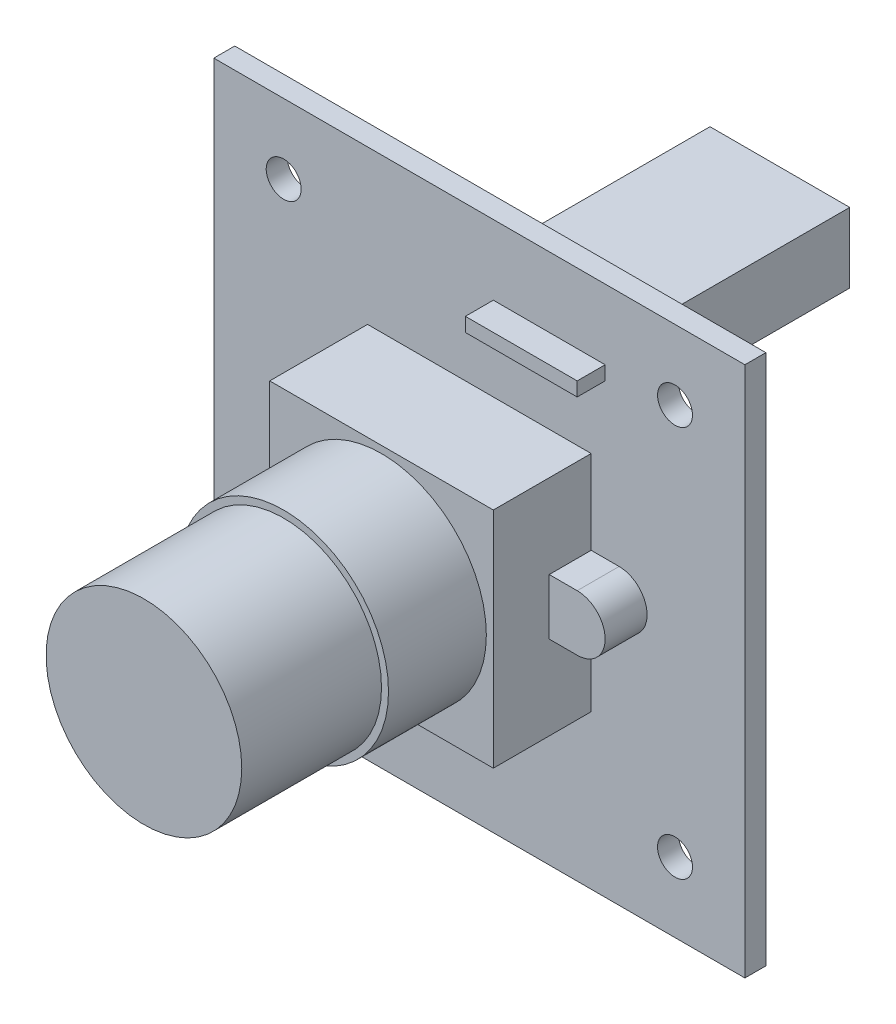
SolidWorks part; units mm, degrees
ref_plane "前视" through (0, 0, 0) normal (0, 0, 1) x (1, 0, 0)
ref_plane "上视" through (0, 0, 0) normal (0, 1, 0) x (1, 0, 0)
ref_plane "右视" through (0, 0, 0) normal (1, 0, 0) x (0, 0, -1)
sketch "草图1" plane through (0, 0, 0) normal (0, 0, 1) x (1, 0, 0)
  line L1 (-19, -19) -> (19, -19)
  line L2 (-19, -19) -> (-19, 19)
  line L3 (-19, 19) -> (19, 19)
  line L4 (19, -19) -> (19, 19)
  line L5 (-19, -19) -> (19, 19) construction
  line L6 (-19, 19) -> (19, -19) construction
  line L7 (-14, -14) -> (14, -14) construction
  line L8 (-14, -14) -> (-14, 14) construction
  line L9 (-14, 14) -> (14, 14) construction
  line L10 (14, -14) -> (14, 14) construction
  line L11 (-14, -14) -> (14, 14) construction
  line L12 (-14, 14) -> (14, -14) construction
  circle A0 centre (-14, 14) radius 1.25
  circle A1 centre (14, 14) radius 1.25
  circle A2 centre (14, -14) radius 1.25
  circle A3 centre (-14, -14) radius 1.25
  point P0 (0, 0)
  point P6 (0, 0)
  dimension "D3" = 2.5
  dimension "D1" = 38
  dimension "D2" = 38
  dimension "D4" = 28
extrude "凸台-拉伸1" add sketch "草图1" along normal blind 1.5
sketch "草图2" plane through (0, 0, 1.5) normal (0, 0, 1) x (1, 0, 0)
  line L1 (8, -8) -> (-8, -8)
  line L2 (8, -8) -> (8, 8)
  line L3 (8, 8) -> (-8, 8)
  line L4 (-8, -8) -> (-8, 8)
  line L5 (8, -8) -> (-8, 8) construction
  line L6 (8, 8) -> (-8, -8) construction
  point P0 (0, 0)
  dimension "D1" = 16
  dimension "D2" = 16
extrude "凸台-拉伸2" add sketch "草图2" along normal blind 7
sketch "草图3" plane through (0, 0, 8.5) normal (0, 0, 1) x (1, 0, 0)
  circle A0 centre (0, 0) radius 7.5
  dimension "D1" = 15
extrude "凸台-拉伸3" add sketch "草图3" along normal blind 7
sketch "草图5" plane through (0, 0, 1.5) normal (0, 0, 1) x (1, 0, 0)
  line L0 (10, 0) -> (-10, 0) construction
  line L1 (10, -2) -> (-10, -2)
  line L2 (10, 2) -> (-10, 2)
  arc A0 (10, -2) -> (10, 2) centre (10, 0) ccw
  arc A1 (-10, 2) -> (-10, -2) centre (-10, 0) ccw
  point P2 (0, 0)
  dimension "D1" = 20
  dimension "D2" = 4
extrude "凸台-拉伸4" add sketch "草图5" along normal blind 3
sketch "草图6" plane through (0, 0, 0) normal (0, 0, -1) x (-1, 0, 0)
  line L1 (-10, 11) -> (0, 11)
  line L2 (-10, 11) -> (-10, 16)
  line L3 (-10, 16) -> (0, 16)
  line L4 (0, 11) -> (0, 16)
  line L5 (-19, 19) -> (19, 19) construction
  line L6 (-19, -19) -> (-19, 19) construction
  dimension "D1" = 9
  dimension "D2" = 3
  dimension "D3" = 10
  dimension "D4" = 5
extrude "凸台-拉伸5" add sketch "草图6" along normal blind 15
sketch "草图7" plane through (0, 0, 15.5) normal (0, 0, 1) x (1, 0, 0)
  circle A0 centre (0, 0) radius 7
  dimension "D1" = 14
extrude "凸台-拉伸6" add sketch "草图7" along normal blind 10
sketch "草图8" plane through (0, 0, 1.5) normal (0, 0, 1) x (1, 0, 0)
  line L0 (10, 16) -> (0, 16) construction
  line L1 (10, 16) -> (0, 16) construction
  line L2 (0, 16) -> (0, 11) construction
  line L3 (0, 16) -> (0, 11) construction
  line L4 (0, 13.5) -> (5, 13.5) construction
  line L5 (5, 13.5) -> (5, 16) construction
  line L7 (9, 14) -> (1, 14)
  line L8 (9, 14) -> (9, 13)
  line L9 (9, 13) -> (1, 13)
  line L10 (1, 14) -> (1, 13)
  line L11 (9, 14) -> (1, 13) construction
  line L12 (9, 13) -> (1, 14) construction
  dimension "D1" = 1
  dimension "D2" = 8
extrude "凸台-拉伸7" add sketch "草图8" along normal blind 2
